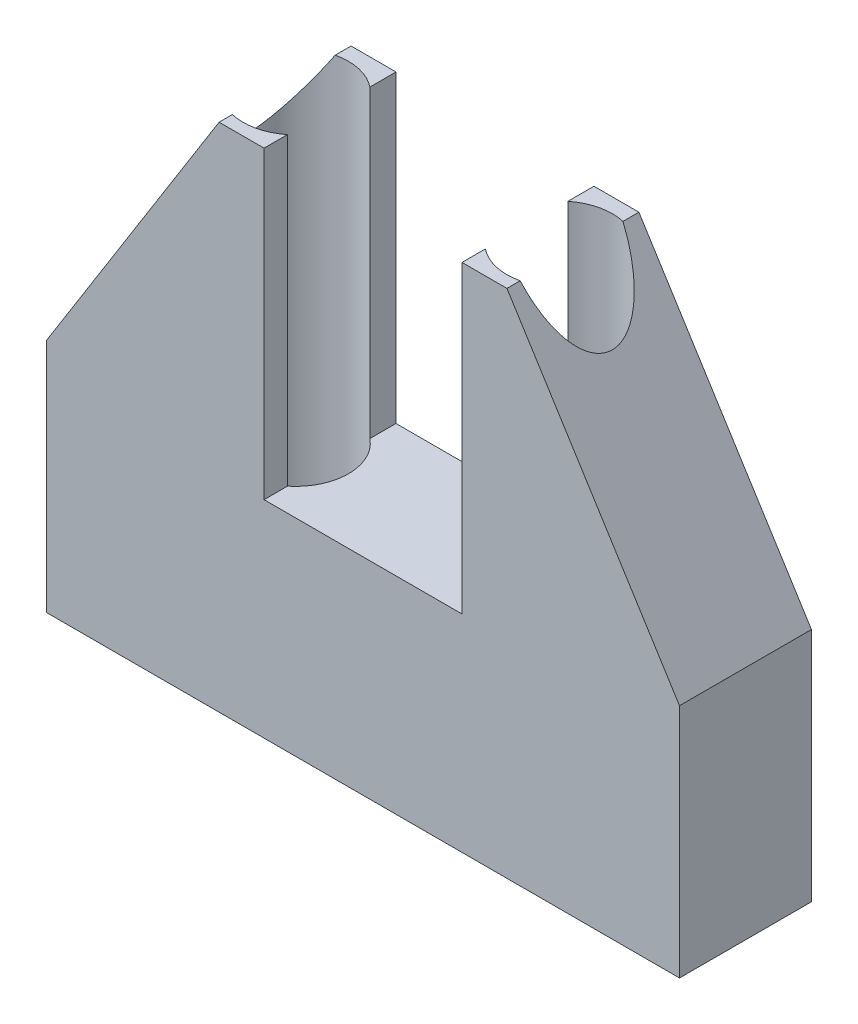
SolidWorks part; units mm, degrees
ref_plane "Front Plane" through (0, 0, 0) normal (0, 0, 1) x (1, 0, 0)
ref_plane "Top Plane" through (0, 0, 0) normal (0, 1, 0) x (1, 0, 0)
ref_plane "Right Plane" through (0, 0, 0) normal (1, 0, 0) x (0, 0, -1)
sketch "Sketch1" plane through (0, 0, 0) normal (0, 0, 1) x (1, 0, 0)
  line L0 (-23.9817, 0) -> (23.9817, 0)
  line L1 (23.9817, 0) -> (23.9817, 17.8696)
  line L2 (23.9817, 17.8696) -> (10.9063, 38.7197)
  line L3 (10.9063, 38.7197) -> (7.5, 38.7197)
  line L4 (7.5, 38.7197) -> (7.5, 15.6494)
  line L5 (7.5, 15.6494) -> (-7.5, 15.6494)
  line L7 (-10.9063, 38.7197) -> (-7.5, 38.7197)
  line L8 (-23.9817, 17.8696) -> (-10.9063, 38.7197)
  line L9 (-23.9817, 0) -> (-23.9817, 17.8696)
  line L10 (-7.5, 38.7197) -> (-7.5, 15.6494)
  point P13 (-6.8663, 16.6633)
  dimension "D1" = 15
extrude "Boss-Extrude1" add sketch "Sketch1" along normal blind 10
hole_wizard "Ø8.0mm Dowel Hole1" positions "Sketch3" profile "Sketch4" hole size "Ø8.0" standard "ANSI Metric" end condition through all
sketch "Sketch3" plane through (0, 0, 0) normal (0, -1, 0) x (-1, 0, 0)
  point P0 (10, -5.1023)
  point P2 (-10, -5.1023)
  dimension "D1" = 20
  dimension "D2" = 10
sketch "Sketch4" plane through (-10, 0, 5.1023) normal (1, 0, 0) x (0, 0, -1)
  line L0 (0, 0) -> (0, 38.7197)
  line L1 (0, 38.7197) -> (4, 38.7197)
  line L2 (4, 38.7197) -> (4, 0)
  line L5 (4, 0) -> (0, 0)
  line L11 (0, -6.35) -> (0, 107.95) construction
  dimension "Thru Hole Dia." = 8
  dimension "Thru Hole Depth" = 38.7197
